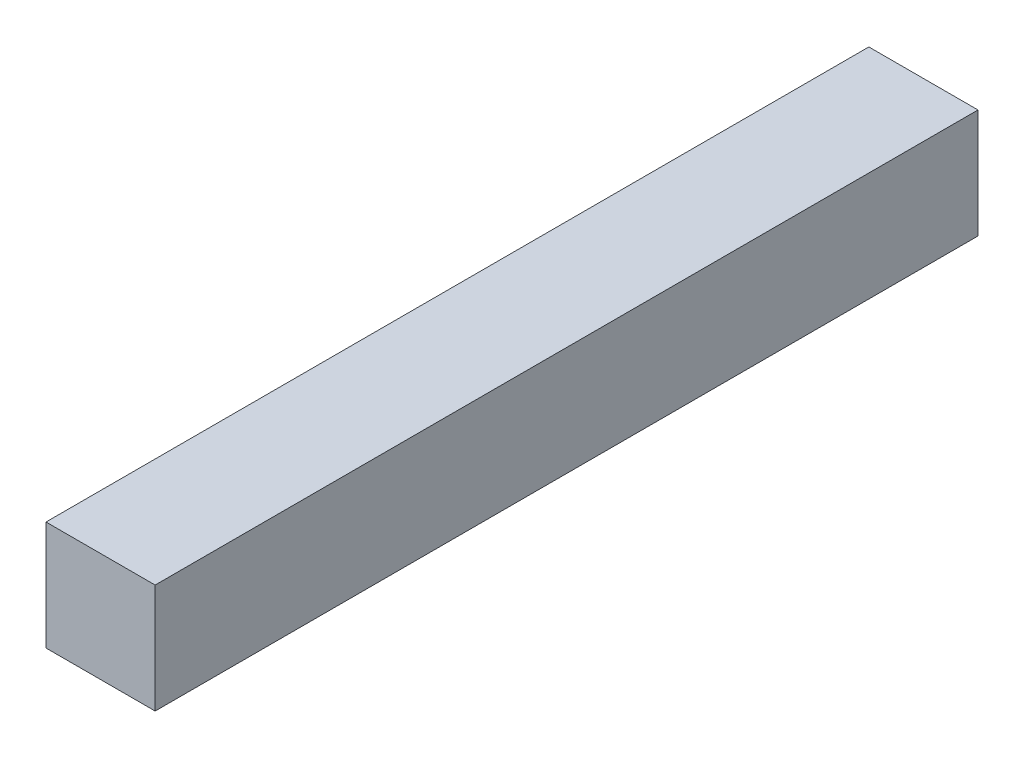
SolidWorks part; units mm, degrees
ref_plane "Front Plane" through (0, 0, 0) normal (0, 0, 1) x (1, 0, 0)
ref_plane "Top Plane" through (0, 0, 0) normal (0, 1, 0) x (1, 0, 0)
ref_plane "Right Plane" through (0, 0, 0) normal (1, 0, 0) x (0, 0, -1)
sketch "Sketch1" plane through (0, 0, 0) normal (0, 0, 1) x (1, 0, 0)
  line L1 (0, 0) -> (13, 0)
  line L2 (0, 0) -> (0, 13)
  line L3 (0, 13) -> (13, 13)
  line L4 (13, 0) -> (13, 13)
  dimension "D1" = 13
  dimension "D2" = 13
extrude "Boss-Extrude1" add sketch "Sketch1" against normal blind 98 contours L4 L3 L2 L1
ref_point "Point1"
